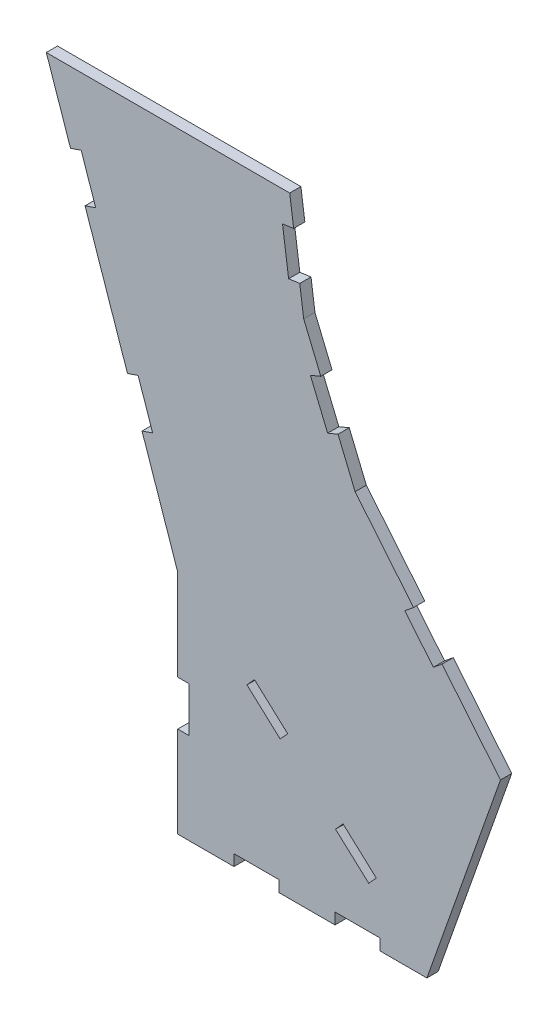
SolidWorks part; units mm, degrees
ref_plane "Přední rovina" through (0, 0, 0) normal (0, 0, 1) x (1, 0, 0)
ref_plane "Horní rovina" through (0, 0, 0) normal (0, 1, 0) x (1, 0, 0)
ref_plane "Pravá rovina" through (0, 0, 0) normal (1, 0, 0) x (0, 0, -1)
sketch "Skica1" plane through (0, 0, 0) normal (0, 0, 1) x (1, 0, 0)
  line L21 (35.099, -102.6197) -> (25.5675, -74.7522)
  line L31 (121.2904, -107.5957) -> (105.6868, -88.6009)
  line L32 (82.4662, -60.3334) -> (77.9028, -49.3274)
  line L33 (68.7433, -27.2365) -> (67.6886, -19.5624)
  line L34 (121.2904, -107.5957) -> (101.6345, -163.2252)
  line L35 (65, 0) -> (0, 0)
  line L36 (101.6345, -163.2252) -> (89.099, -163.2252)
  line L37 (35.099, -163.2252) -> (35.099, -138.9202)
  line L39 (6.4725, -18.9237) -> (9.311, -17.9528)
  line L40 (10.3572, -30.2815) -> (13.1957, -29.3106)
  line L41 (9.311, -17.9528) -> (13.1957, -29.3106)
  line L42 (21.684, -63.398) -> (24.5226, -62.4271)
  line L44 (24.5226, -62.4271) -> (28.4061, -73.7814)
  line L45 (25.5675, -74.7522) -> (28.4061, -73.7814)
  line L46 (21.684, -63.398) -> (10.3572, -30.2815)
  line L47 (6.4725, -18.9237) -> (0, 0)
  line L49 (35.099, -126.9202) -> (38.099, -126.9202)
  line L50 (35.099, -138.9202) -> (38.099, -138.9202)
  line L51 (38.099, -126.9202) -> (38.099, -138.9202)
  line L52 (35.099, -126.9202) -> (35.099, -102.6197)
  line L54 (50.099, -163.2252) -> (50.099, -160.2252)
  line L55 (62.099, -163.2252) -> (62.099, -160.2252)
  line L56 (50.099, -160.2252) -> (62.099, -160.2252)
  line L58 (77.099, -163.2252) -> (77.099, -160.2252)
  line L59 (89.099, -163.2252) -> (89.099, -160.2252)
  line L60 (77.099, -160.2252) -> (89.099, -160.2252)
  line L61 (50.099, -163.2252) -> (35.099, -163.2252)
  line L62 (77.099, -163.2252) -> (62.099, -163.2252)
  line L64 (98.0698, -79.3283) -> (95.7516, -81.2326)
  line L65 (105.6868, -88.6009) -> (103.3687, -90.5051)
  line L66 (95.7516, -81.2326) -> (103.3687, -90.5051)
  line L67 (98.0698, -79.3283) -> (82.4662, -60.3334)
  line L69 (73.3067, -38.2425) -> (70.5355, -39.3915)
  line L70 (77.9028, -49.3274) -> (75.1316, -50.4764)
  line L71 (70.5355, -39.3915) -> (75.1316, -50.4764)
  line L72 (73.3067, -38.2425) -> (68.7433, -27.2365)
  line L74 (66.0547, -7.6741) -> (63.0826, -8.0826)
  line L75 (67.6886, -19.5624) -> (64.7165, -19.9708)
  line L76 (63.0826, -8.0826) -> (64.7165, -19.9708)
  line L77 (66.0547, -7.6741) -> (65, 0)
  line L78 (35.099, -102.6197) -> (101.6345, -163.2252) construction
  line L79 (53.5811, -119.4545) -> (62.4525, -127.5353)
  line L80 (53.5811, -119.4545) -> (55.6013, -117.2367)
  line L81 (62.4525, -127.5353) -> (64.4727, -125.3174)
  line L82 (55.6013, -117.2367) -> (64.4727, -125.3174)
  line L83 (77.2381, -141.0032) -> (86.1095, -149.0839)
  line L84 (77.2381, -141.0032) -> (79.2583, -138.7853)
  line L85 (86.1095, -149.0839) -> (88.1297, -146.8661)
  line L86 (79.2583, -138.7853) -> (88.1297, -146.8661)
  point P1 (11.7765, -29.7961)
  dimension "D4" = 60.6055
  dimension "D5" = 90
  dimension "D7" = 27.4925
  dimension "D8" = 35.8291
  dimension "D1" = 59
  dimension "D2" = 65
  dimension "D3" = 102.6197
  dimension "D6" = 66.5355
  dimension "D9" = 61.1641
  dimension "D10" = 198.882
  dimension "D11" = 109.46
  dimension "D12" = 121.138
  dimension "D13" = 3
  dimension "D14" = 12
  dimension "D15" = 3
  dimension "D16" = 12.0038
  dimension "D17" = 35
  dimension "D18" = 20
  dimension "D19" = 108.4562
  dimension "D20" = 12
  dimension "D21" = 3
  dimension "D22" = 24.305
  dimension "D23" = 3
  dimension "D24" = 3
  dimension "D25" = 12
  dimension "D26" = 12
  dimension "D27" = 15
  dimension "D28" = 15
  dimension "D29" = 3
  dimension "D30" = 12
  dimension "D31" = 24.582
  dimension "D32" = 12
  dimension "D33" = 3
  dimension "D34" = 11.9146
  dimension "D35" = 12
  dimension "D36" = 3
  dimension "D37" = 7.7462
  dimension "D38" = 3
  dimension "D39" = 12
  dimension "D40" = 3
  dimension "D41" = 12
  dimension "D42" = 25
  dimension "D43" = 20
extrude "Přidat vysunutím1" add sketch "Skica1" along normal blind 3
